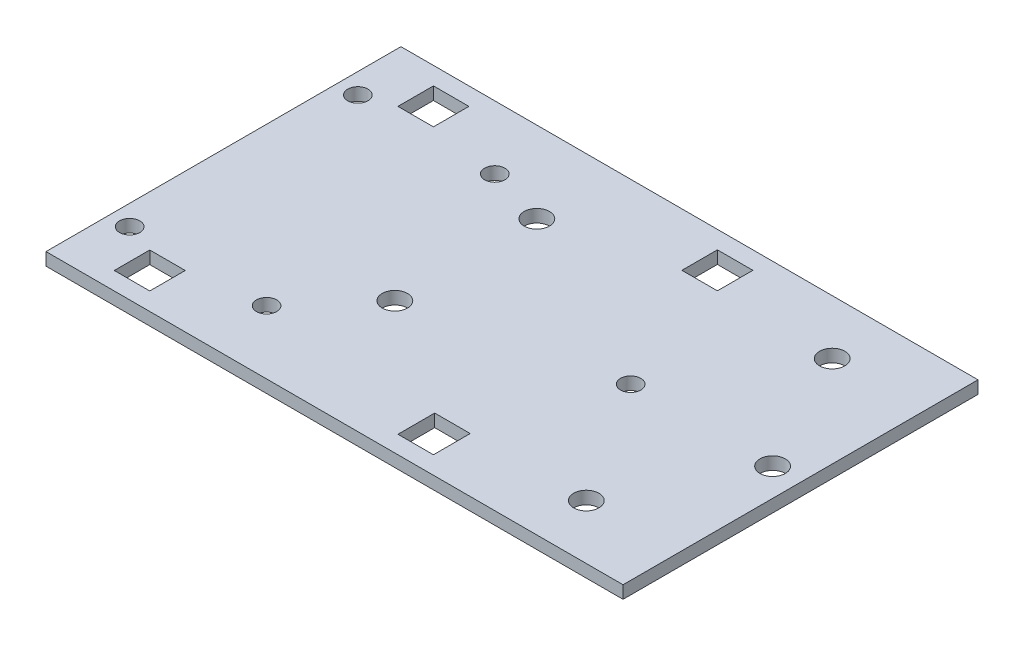
SolidWorks part; units mm, degrees
ref_plane "Front Plane" through (0, 0, 0) normal (0, 0, 1) x (1, 0, 0)
ref_plane "Top Plane" through (0, 0, 0) normal (0, 1, 0) x (1, 0, 0)
ref_plane "Right Plane" through (0, 0, 0) normal (1, 0, 0) x (0, 0, -1)
sketch "Sketch1" plane through (0, 0, 0) normal (0, 1, 0) x (1, 0, 0)
  line L0 (-80.3826, 29.1536) -> (-37.5826, 29.1536)
  line L1 (-80.3826, 29.1536) -> (33.4174, 29.1536)
  line L2 (-80.3826, 29.1536) -> (-80.3826, -40.8464)
  line L3 (-80.3826, -40.8464) -> (33.4174, -40.8464)
  line L4 (33.4174, 29.1536) -> (33.4174, -40.8464)
  line L6 (33.4174, 29.1536) -> (15.4174, 29.1536)
  line L10 (-80.3826, 29.1536) -> (-45.3826, 29.1536)
  line L14 (-80.3826, 29.1536) -> (-80.3826, 4.1536)
  line L15 (-80.3826, -40.8464) -> (-80.3826, -15.8464)
  line L16 (-80.3826, 29.1536) -> (-80.3826, 16.6536)
  line L17 (-80.3826, -40.8464) -> (-80.3826, -28.3464)
  line L22 (-80.3826, 29.1536) -> (-80.3826, 25.6536)
  line L23 (-80.3826, -40.8464) -> (-80.3826, -37.3464)
  line L24 (-80.3826, 25.6536) -> (-63.4776, 25.6536)
  line L25 (-80.3826, -37.3464) -> (-63.4219, -37.3464)
  line L26 (-70.4219, 25.6536) -> (-70.4219, 18.6536)
  line L28 (-70.4219, -37.3464) -> (-63.4219, -37.3464)
  line L29 (-70.4219, -37.3464) -> (-70.4219, -30.3464)
  line L30 (-70.4219, -30.3464) -> (-63.4219, -30.3464)
  line L31 (-63.4219, -37.3464) -> (-63.4219, -30.3464)
  line L34 (-70.4776, 25.6536) -> (-63.4776, 25.6536)
  line L35 (-70.4776, 25.6536) -> (-63.4776, 25.6536)
  line L36 (-70.4776, 25.6536) -> (-70.4776, 18.6536)
  line L37 (-70.4776, 18.6536) -> (-63.4776, 18.6536)
  line L38 (-63.4776, 25.6536) -> (-63.4776, 18.6536)
  line L39 (-7.4776, 25.6536) -> (-7.4776, 18.6536)
  line L40 (33.4174, 29.1536) -> (33.4174, -5.8464)
  line L41 (-7.4776, 25.6536) -> (-14.4776, 25.6536)
  line L42 (-7.4776, 25.6536) -> (-7.4776, 18.6536)
  line L43 (-7.4776, 18.6536) -> (-14.4776, 18.6536)
  line L44 (-14.4776, 25.6536) -> (-14.4776, 18.6536)
  line L45 (-7.4776, -37.3464) -> (-14.4776, -37.3464)
  line L46 (-7.4776, -37.3464) -> (-7.4776, -30.0964)
  line L47 (-7.4776, -30.0964) -> (-14.4776, -30.0964)
  line L48 (-14.4776, -37.3464) -> (-14.4776, -30.0964)
  line L49 (33.4174, -5.8464) -> (30.4198, -5.8464)
  line L50 (33.4174, -5.8464) -> (30.4198, -5.8464)
  line L52 (-70.4219, -30.3464) -> (-70.4219, -37.3464)
  line L57 (-7.4776, -30.0964) -> (-7.4776, -37.3464)
  line L63 (-14.4776, -37.3464) -> (-7.4776, -37.3464)
  line L67 (-14.4776, 25.6536) -> (-7.4776, 25.6536)
  line L68 (-14.4776, 25.6536) -> (-7.4776, 25.6536)
  circle A0 centre (15.4174, 18.4036) radius 2.5
  circle A1 centre (15.4174, -30.0964) radius 2.5
  circle A2 centre (-37.5826, 13.1536) radius 2.5
  circle A3 centre (-37.5826, -14.8464) radius 2.5
  circle A4 centre (-76.3826, 16.6536) radius 2
  circle A5 centre (-76.3826, -28.3464) radius 2
  circle A6 centre (-49.3826, -28.3464) radius 2
  circle A7 centre (-49.3826, 16.6536) radius 2
  circle A8 centre (-0.0826, -5.8464) radius 2
  circle A9 centre (27.9174, -5.8464) radius 2.5024
  dimension "D4" = 48.5
  dimension "D7" = 25
  dimension "D8" = 25
  dimension "D12" = 3.5
  dimension "D16" = 7
  dimension "D1" = 28
  dimension "D2" = 70
  dimension "D3" = 42.8
  dimension "D5" = 53
  dimension "D6" = 35
  dimension "D9" = 12.5
  dimension "D10" = 4
  dimension "D11" = 4
  dimension "D13" = 7
  dimension "D14" = 7
  dimension "D15" = 113.8
  dimension "D17" = 7
  dimension "D18" = 63
  dimension "D19" = 7
  dimension "D20" = 7
  dimension "D21" = 35
  dimension "D22" = 5.5
extrude "Boss-Extrude1" add sketch "Sketch1" along normal blind 2.5
